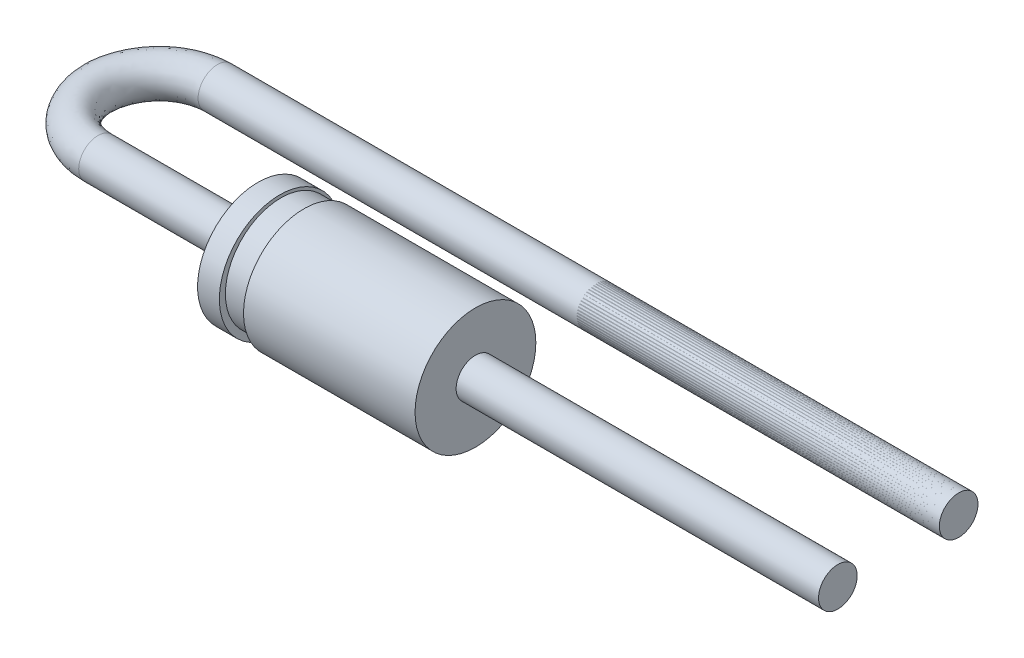
SolidWorks part; units mm, degrees
ref_plane "Front" through (0, 0, 0) normal (0, 0, 1) x (1, 0, 0)
ref_plane "Top" through (0, 0, 0) normal (0, 1, 0) x (1, 0, 0)
ref_plane "Right" through (0, 0, 0) normal (1, 0, 0) x (0, 0, -1)
ref_plane "Плоскость1" through (2.95, 0, 0) normal (1, 0, 0) x (0, 0, -1)
sketch "Эскиз3" plane through (2.95, 0, 0) normal (1, 0, 0) x (0, 0, -1)
  circle A0 centre (-1.525, -0.0336) radius 1.25
  dimension "D2" = 2.5
  dimension "D1" = 1.525
extrude "Вытянуть1" add sketch "Эскиз3" along normal blind 4.5
sketch "Эскиз4" plane through (0, 0, 0) normal (0, 1, 0) x (1, 0, 0)
  line L0 (0, -1.5) -> (10.3423, -1.5) construction
  line L3 (3.4, 0.15) -> (3.9, 0.15)
  line L4 (3.4, 0.15) -> (3.4, -0.35)
  line L5 (3.4, -0.35) -> (3.9, -0.35)
  line L6 (3.9, 0.15) -> (3.9, -0.35)
  dimension "D1" = 1.5
  dimension "D2" = 3.4
  dimension "D3" = 0.5
  dimension "D4" = 0.5
  dimension "D5" = 0.35
revolve "Вырез-Повернуть1" cut sketch "Эскиз4" angle 360 about L0
sketch "Эскиз7" plane through (7.45, 0, 0) normal (1, 0, 0) x (0, 0, -1)
  circle A0 centre (-1.525, -0.0336) radius 0.4
  circle A1 centre (-1.525, -0.0336) radius 1.25 construction
  dimension "D1" = 0.8
extrude "Вытянуть3" add sketch "Эскиз7" along normal blind 7.5
sketch "Эскиз8" plane through (0, 0, 0) normal (0, 1, 0) x (1, 0, 0)
  line L0 (2.95, -1.525) -> (-0.3603, -1.525)
  line L1 (2.95, -0.275) -> (2.95, -2.775) construction
  line L3 (-0.3953, 0.975) -> (14.95, 0.975)
  line L5 (14.95, -1.925) -> (14.95, -1.125) construction
  arc A1 (-0.3603, -1.525) -> (-0.3953, 0.975) centre (-0.3603, -0.2748) cw
  dimension "D1" = 2.5
sketch "Эскиз9" plane through (14.95, 0, 0) normal (1, 0, 0) x (0, 0, -1)
  circle A0 centre (0.975, 0) radius 0.4
  circle A1 centre (-1.525, -0.0336) radius 0.4 construction
surface "Поверхность-По траектории2"
sketch "Эскиз10" plane through (14.95, 0, 0) normal (1, 0, 0) x (0, 0, -1)
  circle A0 centre (0.975, 0) radius 0.4 construction
  circle A1 centre (0.975, 0) radius 0.4
extrude "Вытянуть4" add sketch "Эскиз10" against normal blind 7.5
